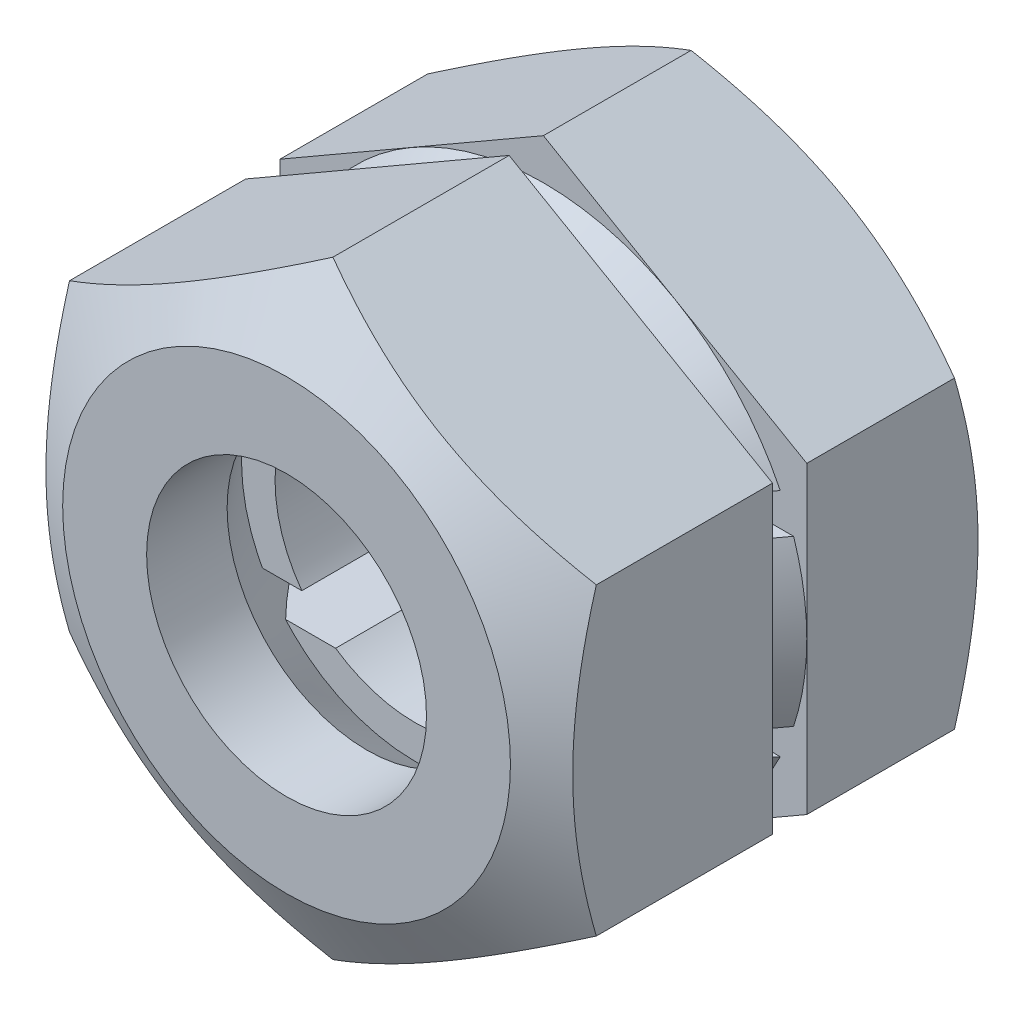
SolidWorks part; units mm, degrees
ref_plane "Přední rovina" through (0, 0, 0) normal (0, 0, 1) x (1, 0, 0)
ref_plane "Vrchní rovina" through (0, 0, 0) normal (0, 1, 0) x (1, 0, 0)
ref_plane "Pravá rovina" through (0, 0, 0) normal (1, 0, 0) x (0, 0, -1)
ref_plane "Rovina1" through (0, 0, 13) normal (0, 0, 1) x (1, 0, 0)
sketch "Skica1" plane through (0, 0, 0) normal (0, 0, 1) x (1, 0, 0)
  line L1 (0, 9.2376) -> (-8, 4.6188)
  line L2 (-8, 4.6188) -> (-8, -4.6188)
  line L3 (-8, -4.6188) -> (0, -9.2376)
  line L4 (0, -9.2376) -> (8, -4.6188)
  line L5 (8, -4.6188) -> (8, 4.6188)
  line L6 (8, 4.6188) -> (0, 9.2376)
  circle A0 centre (0, 0) radius 8 construction
  dimension "s" = 16
extrude "Vysunout1" add sketch "Skica1" along normal blind 5.2
sketch "Skica2" plane through (0, 0, 5.2) normal (0, 0, 1) x (1, 0, 0)
  circle A0 centre (0, 0) radius 8
  dimension "D1" = 16
extrude "Vysunout2" add sketch "Skica2" along normal blind 3.9 draft 35
sketch "Skica3" plane through (0, 0, 13) normal (0, 0, 1) x (1, 0, 0)
  line L7 (8, 4.6188) -> (0, 9.2376)
  line L8 (8, -4.6188) -> (8, 4.6188)
  line L9 (0, -9.2376) -> (8, -4.6188)
  line L10 (-8, -4.6188) -> (0, -9.2376)
  line L11 (-8, 4.6188) -> (-8, -4.6188)
  line L12 (0, 9.2376) -> (-8, 4.6188)
  line L13 (8, 4.6188) -> (0, 9.2376)
  line L14 (8, -4.6188) -> (8, 4.6188)
  line L15 (0, -9.2376) -> (8, -4.6188)
  line L16 (-8, -4.6188) -> (0, -9.2376)
  line L17 (-8, 4.6188) -> (-8, -4.6188)
  line L18 (0, 9.2376) -> (-8, 4.6188)
  dimension "D1" = 0
extrude "Vysunout3" add sketch "Skica3" against normal blind 6.76 separate body
sketch "Skica4" plane through (0, 0, 0) normal (0, 0, -1) x (-1, 0, 0)
  circle A0 centre (0, 0) radius 4.25
  dimension "D1" = 8.5
extrude "Odebrat vysunutím1" cut sketch "Skica4" against normal through all
cosmetic thread "Kosmetický závit1" parameters "D1"=13, "M"=10
sketch "Skica5" plane through (0, 0, 0) normal (0, 1, 0) x (1, 0, 0)
  line L0 (0, 0) -> (0, -5.2) construction
  line L1 (-4, -5.2) -> (0, -5.2) construction
  line L2 (0, -6.24) -> (0, -10.5556)
  line L3 (0, -10.5556) -> (4.25, -10.5556)
  line L4 (4.25, -10.5556) -> (7.2718, -6.24)
  line L5 (7.2718, -6.24) -> (0, -6.24)
  line L6 (5.2692, -9.1) -> (8, -5.2) construction
  line L7 (4.25, -13) -> (4.25, -6.24) construction
revolve "Odebrat rotací1" cut sketch "Skica5" angle 360 about L0
sketch "Skica7" plane through (0, 0, 0) normal (1, 0, 0) x (0, 0, -1)
  line L0 (-11.5926, 9.2376) -> (-13, 6.8)
  line L1 (-6.24, 9.2376) -> (-13, 9.2376) construction
  line L2 (-13, 6.2802) -> (-13, -6.2802) construction
  line L3 (-13, 6.8) -> (-13, 9.2376)
  line L4 (-13, 9.2376) -> (-11.5926, 9.2376)
  line L5 (0, 0) -> (-13, 0) construction
  dimension "D1" = 30
  dimension "D2" = 13.6
revolve "Odebrat rotací2" cut sketch "Skica7" angle 360 about L5
sketch "Skica8" plane through (0, 0, 0) normal (1, 0, 0) x (0, 0, -1)
  line L0 (-0.7145, 9.2376) -> (0, 8)
  line L1 (-5.2, 9.2376) -> (0, 9.2376) construction
  line L2 (0, 4.6188) -> (0, 9.2376) construction
  line L3 (0, 8) -> (0, 9.2376)
  line L4 (0, 9.2376) -> (-0.7145, 9.2376)
  line L5 (0, 0) -> (-5.2, 0) construction
  dimension "D1" = 16
  dimension "D2" = 30
revolve "Odebrat rotací3" cut sketch "Skica8" angle 360 about L5
sketch "Skica9" plane through (0, 0, 0) normal (1, 0, 0) x (0, 0, -1)
  line L0 (-9.1, 5.2692) -> (-9.1, -5.2692) construction
  line L1 (-9.1, 3.5) -> (-5.2, 3.5)
  line L2 (-9.1, 3.5) -> (-9.1, 2.5)
  line L3 (-9.1, 2.5) -> (-5.2, 2.5)
  line L4 (-5.2, 3.5) -> (-5.2, 2.5)
  line L5 (-5.2, 6.9282) -> (-5.2, 0) construction
  line L6 (-5.2, 0) -> (-5.2, -6.9282) construction
  line L7 (-9.1, -2.5) -> (-5.2, -2.5)
  line L8 (-9.1, -2.5) -> (-9.1, -3.5)
  line L9 (-9.1, -3.5) -> (-5.2, -3.5)
  line L10 (-5.2, -2.5) -> (-5.2, -3.5)
  line L11 (0, 0) -> (-5.2, 0) construction
  dimension "D1" = 1
  dimension "D2" = 7
extrude "Odebrat vysunutím2" cut sketch "Skica9" against normal through all and the other way through all
equation "\"D1@Vysunout1\" = \"m@Rovina1\" * 0.4"
equation "\"D1@Skica2\" = \"s@Skica1\""
equation "\"D1@Vysunout2\" = 0.3 * \"m@Rovina1\""
equation "\"D1@Vysunout3\" = 0.52*\"m@Rovina1\""
equation "\"D1@Kosmetický závit1\" = \"m@Rovina1\""
equation "\"D2@Skica7\" = \"s@Skica1\" * 0.85"
equation "\"D1@Skica8\" = \"s@Skica1\""
equation "\"D1@Skica9\" = \"M@Kosmetický závit1\" * 0.1"
equation "\"D2@Skica9\" = \"M@Kosmetický závit1\" * 0.7"
equation "\"D1@Skica4\" = \"M@Kosmetický závit1\" * 0.85"
